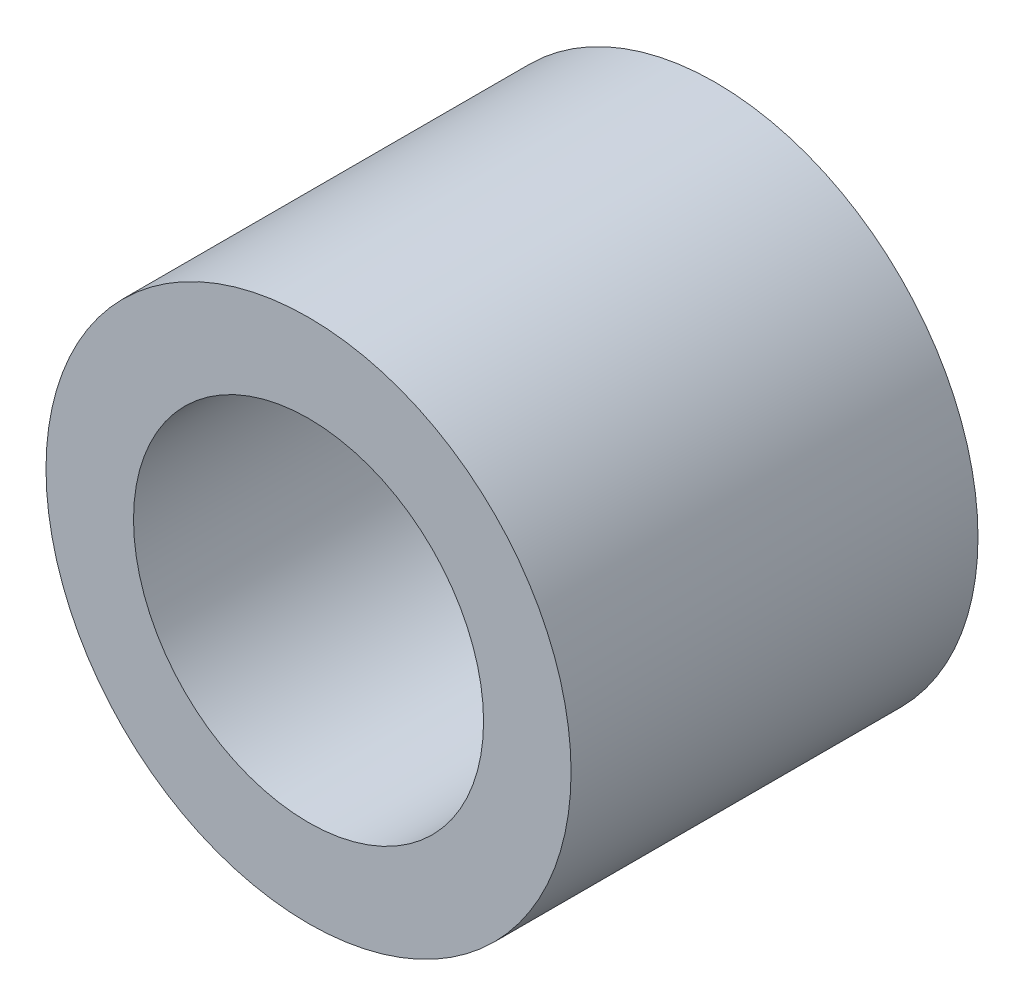
SolidWorks part; units mm, degrees
ref_plane "Płaszczyzna przednia" through (0, 0, 0) normal (0, 0, 1) x (1, 0, 0)
ref_plane "Płaszczyzna górna" through (0, 0, 0) normal (0, 1, 0) x (1, 0, 0)
ref_plane "Płaszczyzna prawa" through (0, 0, 0) normal (1, 0, 0) x (0, 0, -1)
sketch "Szkic1" plane through (0, 0, 0) normal (0, 0, 1) x (1, 0, 0)
  circle A0 centre (0, 0) radius 6
  circle A1 centre (0, 0) radius 9
  dimension "D1" = 12
  dimension "D2" = 18
extrude "Dodanie-wyciągnięcie1" add sketch "Szkic1" along normal blind 13.95
